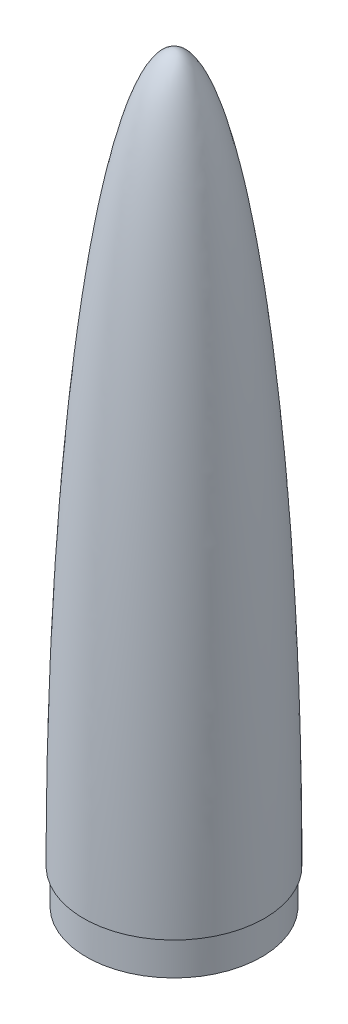
SolidWorks part; units mm, degrees
ref_plane "Alzado" through (0, 0, 0) normal (0, 0, 1) x (1, 0, 0)
ref_plane "Planta" through (0, 0, 0) normal (0, 1, 0) x (1, 0, 0)
ref_plane "Vista lateral" through (0, 0, 0) normal (1, 0, 0) x (0, 0, -1)
sketch "Croquis1" plane through (0, 0, 0) normal (0, 0, 1) x (1, 0, 0)
  line L0 (38.99, 0) -> (-38.99, 0) construction
  line L1 (0, 0) -> (0, 303.8)
  line L2 (38.99, 0) -> (37.79, 0)
  line L3 (0, 305) -> (0, 303.8)
  ellipse E0 centre (0, 0) end of major axis (0, 305) minor radius 38.99 (38.99, 0) -> (0, 305) ccw
  spline S0 degree 1 poles (37.79, 0) (0, 303.8) knots 0 0 1 1 construction
  spline S1 degree 3 poles (37.79, 0) (37.79, 9.9602) (37.6647, 29.9356) (37.1027, 59.5659) (36.1719, 88.6332) (34.4516, 126.2464) (31.432, 170.441) (26.5567, 216.9094) (21.6094, 248.6633) (17.2409, 269.1425) (13.7952, 281.8882) (10.2235, 291.881) (7.1916, 297.8074) (4.8016, 301.0427) (3.0714, 302.7055) (1.4484, 303.6198) (0.5034, 303.8) (0, 303.8) knots -1.570796 -1.570796 -1.570796 -1.570796 -1.472622 -1.374447 -1.276272 -1.178097 -0.981748 -0.785398 -0.589049 -0.490874 -0.392699 -0.294524 -0.19635 -0.147262 -0.098175 -0.049087 0 0 0 0
  point P4 (0, 0)
  dimension "D1" = 77.98
  dimension "D2" = 305
  dimension "D3" = 1.2
revolve "Revolución1" add sketch "Croquis1" angle 360 about L1
sketch "Sketch1" plane through (0, 0, 0) normal (0, 0, 1) x (1, 0, 0)
  line L0 (37.79, 0) -> (37.79, -15)
  line L1 (-38.99, 0) -> (38.99, 0) construction
  line L2 (-37.79, 0) -> (37.79, 0) construction
  line L3 (37.79, -15) -> (36.29, -15)
  line L4 (36.29, -15) -> (36.29, 0)
  line L6 (36.29, 0) -> (36.29, 1.5)
  line L8 (37.79, 1.5) -> (37.79, 0)
  line L9 (0, 0) -> (0, 27.4205) construction
  line L10 (37.79, 3) -> (37.79, 1.5)
  line L12 (37.79, 3) -> (36.29, 1.5)
  dimension "D1" = 15
  dimension "D2" = 1.5
  dimension "D3" = 1.5
  dimension "D4" = 37.79
  dimension "D5" = 3
  dimension "D6" = 1.5
revolve "Revolve1" add sketch "Sketch1" angle 360 about L9
sketch "Sketch2" plane through (0, 0, 0) normal (0, 0, 1) x (1, 0, 0)
  line L0 (-38.8, 0) -> (-38.8, 100) construction
  line L1 (-38.99, 0) -> (38.99, 0) construction
  line L2 (-37.79, 0) -> (37.79, 0) construction
  line L3 (0, 0) -> (0, 100) construction
  line L4 (0, 100) -> (36, 100) construction
  dimension "D1" = 100
  dimension "D2" = 36
